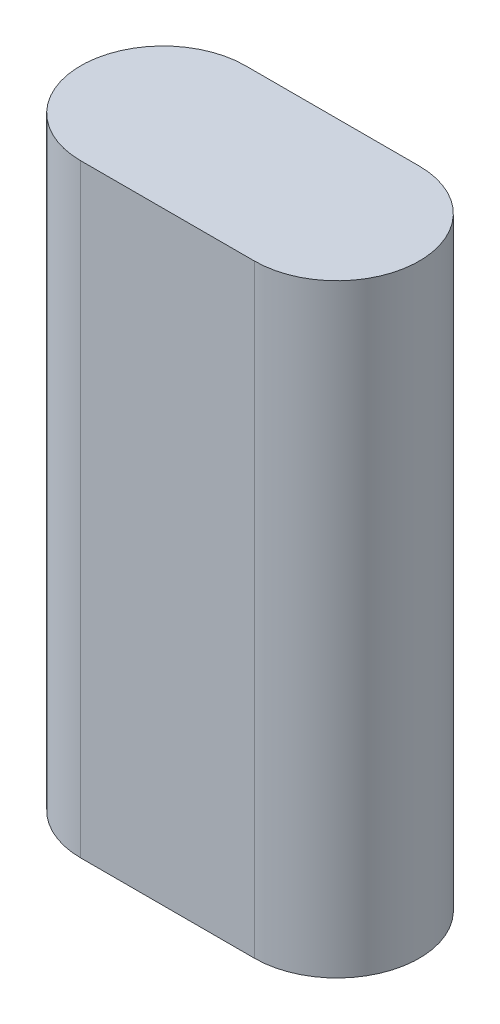
SolidWorks part; units mm, degrees
ref_plane "前视基准面" through (0, 0, 0) normal (0, 0, 1) x (1, 0, 0)
ref_plane "上视基准面" through (0, 0, 0) normal (0, 1, 0) x (1, 0, 0)
ref_plane "右视基准面" through (0, 0, 0) normal (1, 0, 0) x (0, 0, -1)
sketch "草图1" plane through (0, 0, 0) normal (0, 1, 0) x (1, 0, 0)
  line L0 (-9.5, -6) -> (9.5, -6)
  line L1 (-9.5, 9) -> (9.5, 9)
  line L2 (-9.5, 6) -> (9.5, 6)
  line L3 (-9.5, -9) -> (9.5, -9)
  line L5 (-9.5, 9) -> (9.5, -9) construction
  line L6 (-9.5, -9) -> (9.5, 9) construction
  arc A0 (-9.5, 9) -> (-9.5, -9) centre (-9.5, 0) ccw
  arc A1 (9.5, 9) -> (9.5, -9) centre (9.5, 0) cw
  arc A2 (-9.5, 6) -> (-9.5, -6) centre (-9.5, 0) ccw
  arc A3 (9.5, 6) -> (9.5, -6) centre (9.5, 0) cw
  point P0 (0, 0)
  dimension "D1" = 18
  dimension "D2" = 19
  dimension "D3" = 3
extrude "凸台-拉伸1" add sketch "草图1" along normal blind 66 contours A0 L3 A1 L1
